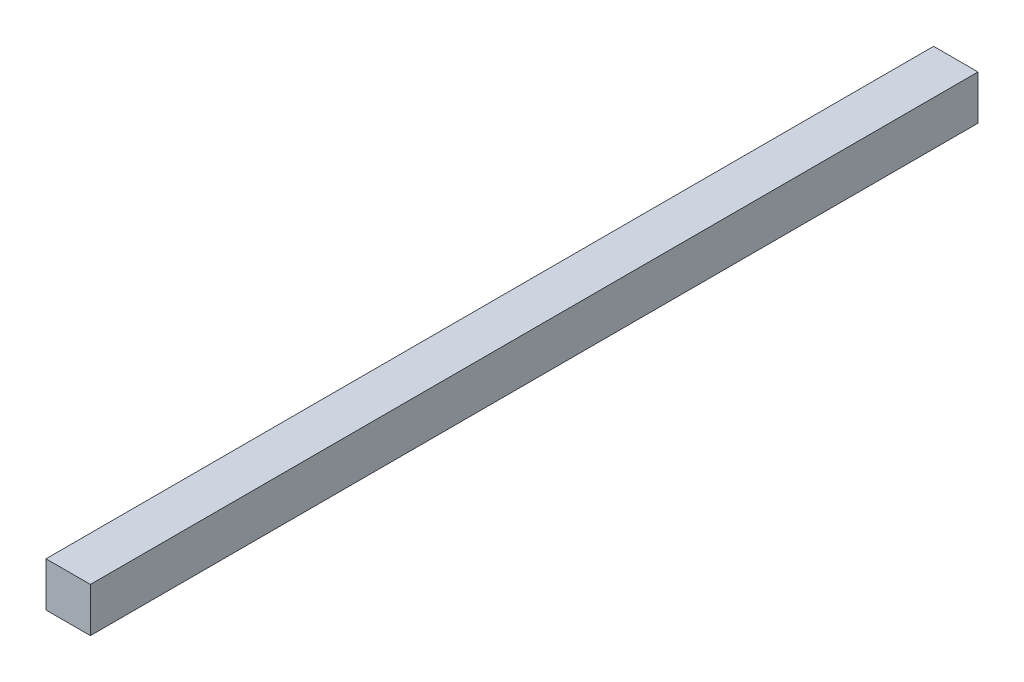
SolidWorks part; units mm, degrees
ref_plane "Front Plane" through (0, 0, 0) normal (0, 0, 1) x (1, 0, 0)
ref_plane "Top Plane" through (0, 0, 0) normal (0, 1, 0) x (1, 0, 0)
ref_plane "Right Plane" through (0, 0, 0) normal (1, 0, 0) x (0, 0, -1)
sketch "Sketch1" plane through (0, 0, 0) normal (0, 0, 1) x (1, 0, 0)
  line L1 (-10, -10) -> (10, -10)
  line L2 (-10, -10) -> (-10, 10)
  line L3 (-10, 10) -> (10, 10)
  line L4 (10, -10) -> (10, 10)
  line L5 (-10, -10) -> (10, 10) construction
  line L6 (-10, 10) -> (10, -10) construction
  point P0 (0, 0)
  dimension "D1" = 20
extrude "Boss-Extrude1" add sketch "Sketch1" along normal blind 400
